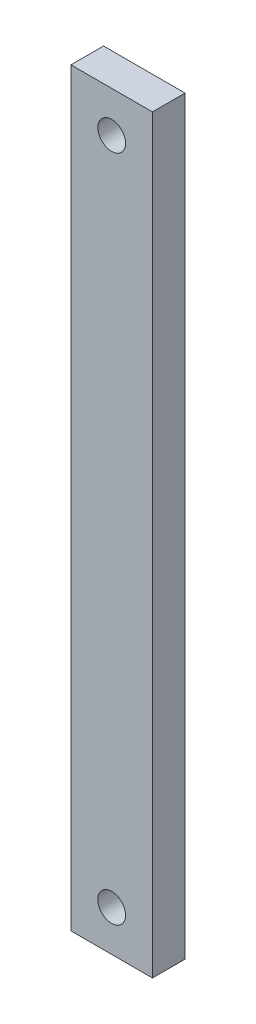
SolidWorks part; units mm, degrees
ref_plane "前视基准面" through (0, 0, 0) normal (0, 0, 1) x (1, 0, 0)
ref_plane "上视基准面" through (0, 0, 0) normal (0, 1, 0) x (1, 0, 0)
ref_plane "右视基准面" through (0, 0, 0) normal (1, 0, 0) x (0, 0, -1)
other "Configuration Table"
sketch "草图1" plane through (0, 0, 0) normal (0, 0, 1) x (1, 0, 0)
  line L1 (75, -46) -> (85, -46)
  line L2 (75, -46) -> (75, 46)
  line L3 (75, 46) -> (85, 46)
  line L4 (85, -46) -> (85, 46)
extrude "Control_battery_clamp" add sketch "草图1" along normal blind 4 from offset 94
sketch "草图2" plane through (0, 0, 0) normal (0, 0, 1) x (1, 0, 0)
  circle A0 centre (80, -41) radius 1.7
  circle A1 centre (80, 41) radius 1.7
extrude "Clamp_two_M3" cut sketch "草图2" against normal blind 6 from offset 99
